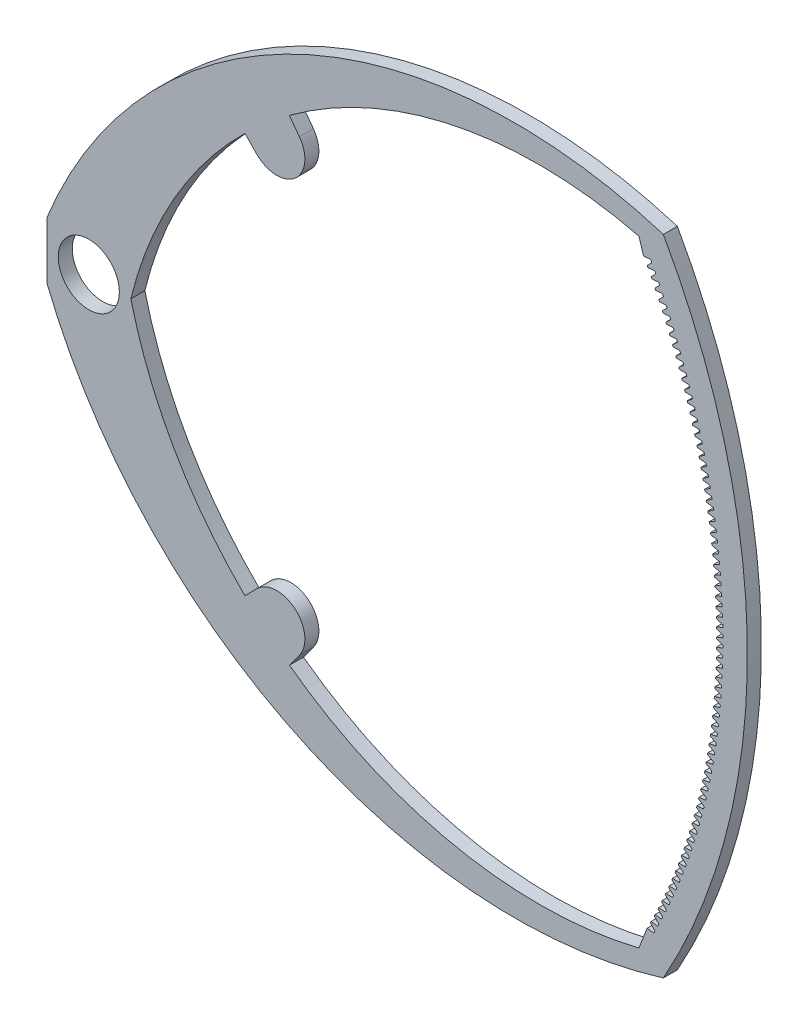
SolidWorks part; units mm, degrees
ref_plane "Plane1" through (0, 0, 0) normal (0, 0, 1) x (1, 0, 0)
ref_plane "Plane2" through (0, 0, 0) normal (0, 1, 0) x (1, 0, 0)
ref_plane "Plane3" through (0, 0, 0) normal (1, 0, 0) x (0, 0, -1)
sketch "Sketch3" plane through (0, 0, 0) normal (0, 0, 1) x (1, 0, 0)
  line L0 (0, 0) -> (305.6191, 0) construction
  line L2 (196.2779, 110) -> (205.0013, 114.8889) construction
  line L5 (-15, -10) -> (-15, 10)
  line L12 (55.7183, 71.4371) -> (59.917, 67.151)
  line L13 (59.917, 67.151) -> (75.1416, 80.1207) construction
  line L14 (75.1416, 80.1207) -> (71.5772, 84.9472)
  line L15 (71.5772, 84.9472) -> (38.0851, 60.2137) construction
  line L16 (55.7183, 71.4371) -> (7.4774, 24.1803) construction
  line L17 (75.1416, -80.1207) -> (71.5772, -84.9472)
  line L18 (55.7183, -71.4371) -> (59.917, -67.151)
  line L19 (226.2435, 1.7084) -> (223.986, 2.5016)
  line L20 (224, 0) -> (226.2485, 0.8184)
  line L21 (224.9781, 3.1415) -> (0, 0) construction
  line L22 (223.9782, 3.1275) -> (226.215, 3.9772)
  line L23 (226.1976, 4.8671) -> (223.9293, 5.6287)
  line L24 (223.9127, 6.2544) -> (226.1375, 7.1353)
  line L25 (226.1076, 8.0248) -> (223.8289, 8.7547)
  line L26 (223.8035, 9.3801) -> (226.0158, 10.292)
  line L27 (225.9736, 11.181) -> (223.6848, 11.879)
  line L28 (223.6507, 12.504) -> (225.8501, 13.4467)
  line L29 (225.7954, 14.335) -> (223.4971, 15.001)
  line L30 (223.4543, 15.6255) -> (225.6403, 16.5987)
  line L31 (225.5733, 17.4862) -> (223.2659, 18.12)
  line L32 (223.2144, 18.7438) -> (225.3866, 19.7475)
  line L33 (225.3071, 20.634) -> (222.9911, 21.2355)
  line L34 (222.9309, 21.8586) -> (225.0889, 22.8925)
  line L35 (224.9971, 23.7777) -> (222.6729, 24.3469)
  line L36 (222.604, 24.969) -> (224.7473, 26.033)
  line L37 (224.6431, 26.9169) -> (222.3113, 27.4535)
  line L38 (222.2337, 28.0746) -> (224.3619, 29.1684)
  line L39 (224.2454, 30.0508) -> (221.9063, 30.5548)
  line L40 (221.82, 31.1748) -> (223.9328, 32.2981)
  line L41 (223.804, 33.1788) -> (221.4581, 33.6501)
  line L42 (221.3632, 34.2688) -> (223.46, 35.4216)
  line L43 (223.3189, 36.3003) -> (220.9666, 36.7389)
  line L44 (220.8631, 37.3562) -> (222.9437, 38.5381)
  line L45 (222.7903, 39.4148) -> (220.4321, 39.8205)
  line L46 (220.32, 40.4363) -> (222.3839, 41.6471)
  line L47 (222.2183, 42.5216) -> (219.8547, 42.8943)
  line L48 (219.734, 43.5085) -> (221.7807, 44.748)
  line L49 (221.6029, 45.6201) -> (219.2343, 45.9598)
  line L50 (219.1051, 46.5722) -> (221.1343, 47.8402)
  line L51 (220.9444, 48.7097) -> (218.5713, 49.0163)
  line L52 (218.4335, 49.6269) -> (220.4448, 50.9231)
  line L53 (220.2428, 51.7899) -> (217.8656, 52.0632)
  line L54 (217.7193, 52.6718) -> (219.7123, 53.996)
  line L55 (219.4982, 54.8599) -> (217.1174, 55.1)
  line L56 (216.9626, 55.7065) -> (218.937, 57.0584)
  line L57 (218.7108, 57.9192) -> (216.327, 58.1261)
  line L58 (216.1637, 58.7304) -> (218.119, 60.1097)
  line L59 (217.8808, 60.9672) -> (215.4943, 61.1408)
  line L60 (215.3226, 61.7428) -> (217.2585, 63.1492)
  line L61 (217.0084, 64.0034) -> (214.6196, 64.1436)
  line L62 (214.4396, 64.7431) -> (216.3556, 66.1765)
  line L63 (216.0936, 67.0271) -> (213.7031, 67.1339)
  line L64 (213.5147, 67.7309) -> (215.4105, 69.1908)
  line L65 (215.1367, 70.0377) -> (212.745, 70.1112)
  line L66 (212.5482, 70.7054) -> (214.4235, 72.1917)
  line L67 (214.1378, 73.0346) -> (211.7453, 73.0747)
  line L68 (211.5403, 73.6661) -> (213.3946, 75.1785)
  line L69 (213.0972, 76.0173) -> (210.7044, 76.024)
  line L70 (210.4911, 76.6125) -> (212.3242, 78.1506)
  line L71 (212.0151, 78.9852) -> (209.6224, 78.9585)
  line L72 (209.401, 79.544) -> (211.2123, 81.1075)
  line L73 (210.8916, 81.9377) -> (208.4995, 81.8776)
  line L74 (208.2699, 82.4599) -> (210.0593, 84.0486)
  line L75 (209.727, 84.8742) -> (207.336, 84.7807)
  line L76 (207.0983, 85.3598) -> (208.8653, 86.9733)
  line L77 (208.5216, 87.7942) -> (206.1321, 87.6673)
  line L78 (205.8863, 88.243) -> (207.6306, 89.881)
  line L79 (207.2754, 90.6971) -> (204.888, 90.5368)
  line L80 (204.6342, 91.109) -> (206.3554, 92.7712)
  line L81 (205.9889, 93.5822) -> (203.6039, 93.3887)
  line L82 (203.3422, 93.9573) -> (205.04, 95.6433)
  line L83 (204.6622, 96.4492) -> (202.2802, 96.2223)
  line L84 (202.0105, 96.7872) -> (203.6847, 98.4968)
  line L85 (203.2956, 99.2973) -> (200.917, 99.0372)
  line L86 (200.6394, 99.5983) -> (202.2896, 101.3311)
  line L87 (201.8894, 102.1261) -> (199.5146, 101.8328)
  line L88 (199.2293, 102.3899) -> (200.8551, 104.1456)
  line L89 (200.4438, 104.9349) -> (198.0734, 104.6085)
  line L90 (197.7803, 105.1616) -> (196.2779, 110)
  line L91 (226.2453, -1.4506) -> (223.9991, -0.626)
  line L92 (223.9782, -3.1275) -> (226.2379, -2.3406)
  line L93 (226.203, -4.6094) -> (223.9686, -3.7534)
  line L94 (223.9127, -6.2544) -> (226.1832, -5.4992)
  line L95 (226.1166, -7.7672) -> (223.8943, -6.8801)
  line L96 (223.8035, -9.3801) -> (226.0843, -8.6566)
  line L97 (225.9861, -10.9235) -> (223.7764, -10.0055)
  line L98 (223.6507, -12.504) -> (225.9414, -11.8124)
  line L99 (225.8116, -14.0777) -> (223.6149, -13.1289)
  line L100 (223.4543, -15.6255) -> (225.7545, -14.9659)
  line L101 (225.593, -17.2292) -> (223.4098, -16.2498)
  line L102 (223.2144, -18.7438) -> (225.5235, -18.1165)
  line L103 (225.3305, -20.3773) -> (223.1612, -19.3675)
  line L104 (222.9309, -21.8586) -> (225.2486, -21.2635)
  line L105 (225.024, -23.5214) -> (222.869, -22.4814)
  line L106 (222.604, -24.969) -> (224.9297, -24.4064)
  line L107 (224.6737, -26.6609) -> (222.5334, -25.591)
  line L108 (222.2337, -28.0746) -> (224.5671, -27.5445)
  line L109 (224.2795, -29.7952) -> (222.1544, -28.6955)
  line L110 (221.82, -31.1748) -> (224.1606, -30.6773)
  line L111 (223.8417, -32.9238) -> (221.7321, -31.7945)
  line L112 (221.3632, -34.2688) -> (223.7104, -33.8041)
  line L113 (223.3602, -36.0459) -> (221.2665, -34.8873)
  line L114 (220.8631, -37.3562) -> (223.2166, -36.9242)
  line L115 (222.8351, -39.161) -> (220.7579, -37.9732)
  line L116 (220.32, -40.4363) -> (222.6793, -40.0372)
  line L117 (222.2666, -42.2684) -> (220.2062, -41.0518)
  line L118 (219.734, -43.5085) -> (222.0986, -43.1424)
  line L119 (221.6548, -45.3676) -> (219.6115, -44.1224)
  line L120 (219.1051, -46.5722) -> (221.4746, -46.2392)
  line L121 (220.9997, -48.458) -> (218.9741, -47.1843)
  line L122 (218.4335, -49.6269) -> (220.8074, -49.327)
  line L123 (220.3016, -51.5389) -> (218.2939, -50.2371)
  line L124 (217.7193, -52.6718) -> (220.0972, -52.4051)
  line L125 (219.5606, -54.6098) -> (217.5712, -53.28)
  line L126 (216.9626, -55.7065) -> (219.344, -55.473)
  line L127 (218.7767, -57.67) -> (216.8061, -56.3126)
  line L128 (216.1637, -58.7304) -> (218.5481, -58.5301)
  line L129 (217.9502, -60.719) -> (215.9987, -59.3342)
  line L130 (215.3226, -61.7428) -> (217.7096, -61.5759)
  line L131 (217.0811, -63.7561) -> (215.1492, -62.3442)
  line L132 (214.4396, -64.7431) -> (216.8287, -64.6096)
  line L133 (216.1698, -66.7808) -> (214.2578, -65.3421)
  line L134 (213.5147, -67.7309) -> (215.9054, -67.6307)
  line L135 (215.2163, -69.7925) -> (213.3246, -68.3272)
  line L136 (212.5482, -70.7054) -> (214.9401, -70.6386)
  line L137 (214.2209, -72.7906) -> (212.3498, -71.2991)
  line L138 (211.5403, -73.6661) -> (213.9329, -73.6327)
  line L139 (213.1837, -75.7745) -> (211.3336, -74.257)
  line L140 (210.4911, -76.6125) -> (212.884, -76.6125)
  line L141 (212.1049, -78.7436) -> (210.2762, -77.2004)
  line L142 (209.401, -79.544) -> (211.7935, -79.5774)
  line L143 (210.9848, -81.6974) -> (209.1779, -80.1288)
  line L144 (208.2699, -82.4599) -> (210.6618, -82.5267)
  line L145 (209.8236, -84.6352) -> (208.0387, -83.0416)
  line L146 (207.0983, -85.3598) -> (209.489, -85.46)
  line L147 (208.6215, -87.5566) -> (206.859, -85.9382)
  line L148 (205.8863, -88.243) -> (208.2754, -88.3766)
  line L149 (207.3786, -90.4608) -> (205.6389, -88.818)
  line L150 (204.6342, -91.109) -> (207.0212, -91.2759)
  line L151 (206.0954, -93.3475) -> (204.3788, -91.6805)
  line L152 (203.3422, -93.9573) -> (205.7266, -94.1575)
  line L153 (204.772, -96.2159) -> (203.0788, -94.5251)
  line L154 (202.0105, -96.7872) -> (204.3919, -97.0207)
  line L155 (203.4086, -99.0656) -> (201.7392, -97.3513)
  line L156 (200.6394, -99.5983) -> (203.0173, -99.865)
  line L157 (202.0056, -101.896) -> (200.3603, -100.1586)
  line L158 (199.2293, -102.3899) -> (201.6032, -102.6898)
  line L159 (199.2293, -102.3899) -> (196.2779, -110)
  arc A0 (205.0013, -114.8889) -> (205.0013, 114.8889) centre (0, 0) ccw
  arc A1 (220.8879, 48.9651) -> (225.6282, -16.7623) centre (0, 0) cw construction
  arc A2 (196.2779, 110) -> (196.2779, -110) centre (0, 0) cw construction
  circle A3 centre (0, 0) radius 10.9
  circle A4 centre (100, 0) radius 70 construction
  arc A5 (15, 0) -> (196.2779, 110) centre (160.6858, -35.7162) cw construction
  arc A6 (-15, 10) -> (205.0013, 114.8889) centre (152.0118, -57.1347) cw
  arc A7 (-15, -10) -> (205.0013, -114.8889) centre (152.0118, 57.1347) ccw
  arc A9 (15, 0) -> (55.7183, 71.4371) centre (160.6858, -35.7162) cw
  arc A10 (71.5772, 84.9472) -> (196.2779, 110) centre (160.6858, -35.7162) cw
  arc A11 (75.1416, 80.1207) -> (59.917, 67.151) centre (67.0779, 74.1658) cw
  arc A12 (100, 0) -> (46.366, 88.6013) centre (0, 0) ccw construction
  arc A13 (71.5772, -84.9472) -> (196.2779, -110) centre (160.6858, 35.7162) ccw
  arc A14 (75.1416, -80.1207) -> (59.917, -67.151) centre (67.0779, -74.1658) ccw
  arc A15 (15, 0) -> (55.7183, -71.4371) centre (160.6858, 35.7162) ccw
  arc A16 (223.2671, -18.1055) -> (218.4, 49.774) centre (0, 0) ccw construction
  arc A17 (223.9782, 3.1275) -> (223.986, 2.5016) centre (0, 0) cw
  arc A18 (226.2485, 0.8184) -> (226.2435, 1.7084) centre (0, 0) ccw
  arc A19 (226.215, 3.9772) -> (226.1976, 4.8671) centre (0, 0) ccw
  arc A20 (223.9127, 6.2544) -> (223.9293, 5.6287) centre (0, 0) cw
  arc A21 (226.1375, 7.1353) -> (226.1076, 8.0248) centre (0, 0) ccw
  arc A22 (223.8035, 9.3801) -> (223.8289, 8.7547) centre (0, 0) cw
  arc A23 (226.0158, 10.292) -> (225.9736, 11.181) centre (0, 0) ccw
  arc A24 (223.6507, 12.504) -> (223.6848, 11.879) centre (0, 0) cw
  arc A25 (225.8501, 13.4467) -> (225.7954, 14.335) centre (0, 0) ccw
  arc A26 (223.4543, 15.6255) -> (223.4971, 15.001) centre (0, 0) cw
  arc A27 (225.6403, 16.5987) -> (225.5733, 17.4862) centre (0, 0) ccw
  arc A28 (223.2144, 18.7438) -> (223.2659, 18.12) centre (0, 0) cw
  arc A29 (225.3866, 19.7475) -> (225.3071, 20.634) centre (0, 0) ccw
  arc A30 (222.9309, 21.8586) -> (222.9911, 21.2355) centre (0, 0) cw
  arc A31 (225.0889, 22.8925) -> (224.9971, 23.7777) centre (0, 0) ccw
  arc A32 (222.604, 24.969) -> (222.6729, 24.3469) centre (0, 0) cw
  arc A33 (224.7473, 26.033) -> (224.6431, 26.9169) centre (0, 0) ccw
  arc A34 (222.2337, 28.0746) -> (222.3113, 27.4535) centre (0, 0) cw
  arc A35 (224.3619, 29.1684) -> (224.2454, 30.0508) centre (0, 0) ccw
  arc A36 (221.82, 31.1748) -> (221.9063, 30.5548) centre (0, 0) cw
  arc A37 (223.9328, 32.2981) -> (223.804, 33.1788) centre (0, 0) ccw
  arc A38 (221.3632, 34.2688) -> (221.4581, 33.6501) centre (0, 0) cw
  arc A39 (223.46, 35.4216) -> (223.3189, 36.3003) centre (0, 0) ccw
  arc A40 (220.8631, 37.3562) -> (220.9666, 36.7389) centre (0, 0) cw
  arc A41 (222.9437, 38.5381) -> (222.7903, 39.4148) centre (0, 0) ccw
  arc A42 (220.32, 40.4363) -> (220.4321, 39.8205) centre (0, 0) cw
  arc A43 (222.3839, 41.6471) -> (222.2183, 42.5216) centre (0, 0) ccw
  arc A44 (219.734, 43.5085) -> (219.8547, 42.8943) centre (0, 0) cw
  arc A45 (221.7807, 44.748) -> (221.6029, 45.6201) centre (0, 0) ccw
  arc A46 (219.1051, 46.5722) -> (219.2343, 45.9598) centre (0, 0) cw
  arc A47 (221.1343, 47.8402) -> (220.9444, 48.7097) centre (0, 0) ccw
  arc A48 (218.4335, 49.6269) -> (218.5713, 49.0163) centre (0, 0) cw
  arc A49 (220.4448, 50.9231) -> (220.2428, 51.7899) centre (0, 0) ccw
  arc A50 (217.7193, 52.6718) -> (217.8656, 52.0632) centre (0, 0) cw
  arc A51 (219.7123, 53.996) -> (219.4982, 54.8599) centre (0, 0) ccw
  arc A52 (216.9626, 55.7065) -> (217.1174, 55.1) centre (0, 0) cw
  arc A53 (218.937, 57.0584) -> (218.7108, 57.9192) centre (0, 0) ccw
  arc A54 (216.1637, 58.7304) -> (216.327, 58.1261) centre (0, 0) cw
  arc A55 (218.119, 60.1097) -> (217.8808, 60.9672) centre (0, 0) ccw
  arc A56 (215.3226, 61.7428) -> (215.4943, 61.1408) centre (0, 0) cw
  arc A57 (217.2585, 63.1492) -> (217.0084, 64.0034) centre (0, 0) ccw
  arc A58 (214.4396, 64.7431) -> (214.6196, 64.1436) centre (0, 0) cw
  arc A59 (216.3556, 66.1765) -> (216.0936, 67.0271) centre (0, 0) ccw
  arc A60 (213.5147, 67.7309) -> (213.7031, 67.1339) centre (0, 0) cw
  arc A61 (215.4105, 69.1908) -> (215.1367, 70.0377) centre (0, 0) ccw
  arc A62 (212.5482, 70.7054) -> (212.745, 70.1112) centre (0, 0) cw
  arc A63 (214.4235, 72.1917) -> (214.1378, 73.0346) centre (0, 0) ccw
  arc A64 (211.5403, 73.6661) -> (211.7453, 73.0747) centre (0, 0) cw
  arc A65 (213.3946, 75.1785) -> (213.0972, 76.0173) centre (0, 0) ccw
  arc A66 (210.4911, 76.6125) -> (210.7044, 76.024) centre (0, 0) cw
  arc A67 (212.3242, 78.1506) -> (212.0151, 78.9852) centre (0, 0) ccw
  arc A68 (209.401, 79.544) -> (209.6224, 78.9585) centre (0, 0) cw
  arc A69 (211.2123, 81.1075) -> (210.8916, 81.9377) centre (0, 0) ccw
  arc A70 (208.2699, 82.4599) -> (208.4995, 81.8776) centre (0, 0) cw
  arc A71 (210.0593, 84.0486) -> (209.727, 84.8742) centre (0, 0) ccw
  arc A72 (207.0983, 85.3598) -> (207.336, 84.7807) centre (0, 0) cw
  arc A73 (208.8653, 86.9733) -> (208.5216, 87.7942) centre (0, 0) ccw
  arc A74 (205.8863, 88.243) -> (206.1321, 87.6673) centre (0, 0) cw
  arc A75 (207.6306, 89.881) -> (207.2754, 90.6971) centre (0, 0) ccw
  arc A76 (204.6342, 91.109) -> (204.888, 90.5368) centre (0, 0) cw
  arc A77 (206.3554, 92.7712) -> (205.9889, 93.5822) centre (0, 0) ccw
  arc A78 (203.3422, 93.9573) -> (203.6039, 93.3887) centre (0, 0) cw
  arc A79 (205.04, 95.6433) -> (204.6622, 96.4492) centre (0, 0) ccw
  arc A80 (202.0105, 96.7872) -> (202.2802, 96.2223) centre (0, 0) cw
  arc A81 (203.6847, 98.4968) -> (203.2956, 99.2973) centre (0, 0) ccw
  arc A82 (200.6394, 99.5983) -> (200.917, 99.0372) centre (0, 0) cw
  arc A83 (202.2896, 101.3311) -> (201.8894, 102.1261) centre (0, 0) ccw
  arc A84 (199.2293, 102.3899) -> (199.5146, 101.8328) centre (0, 0) cw
  arc A85 (200.8551, 104.1456) -> (200.4438, 104.9349) centre (0, 0) ccw
  arc A86 (197.7803, 105.1616) -> (198.0734, 104.6085) centre (0, 0) cw
  arc A87 (224, 0) -> (223.9991, -0.626) centre (0, 0) cw
  arc A88 (226.2379, -2.3406) -> (226.2453, -1.4506) centre (0, 0) ccw
  arc A89 (223.9782, -3.1275) -> (223.9686, -3.7534) centre (0, 0) cw
  arc A90 (226.1832, -5.4992) -> (226.203, -4.6094) centre (0, 0) ccw
  arc A91 (223.9127, -6.2544) -> (223.8943, -6.8801) centre (0, 0) cw
  arc A92 (226.0843, -8.6566) -> (226.1166, -7.7672) centre (0, 0) ccw
  arc A93 (223.8035, -9.3801) -> (223.7764, -10.0055) centre (0, 0) cw
  arc A94 (225.9414, -11.8124) -> (225.9861, -10.9235) centre (0, 0) ccw
  arc A95 (223.6507, -12.504) -> (223.6149, -13.1289) centre (0, 0) cw
  arc A96 (225.7545, -14.9659) -> (225.8116, -14.0777) centre (0, 0) ccw
  arc A97 (223.4543, -15.6255) -> (223.4098, -16.2498) centre (0, 0) cw
  arc A98 (225.5235, -18.1165) -> (225.593, -17.2292) centre (0, 0) ccw
  arc A99 (223.2144, -18.7438) -> (223.1612, -19.3675) centre (0, 0) cw
  arc A100 (225.2486, -21.2635) -> (225.3305, -20.3773) centre (0, 0) ccw
  arc A101 (222.9309, -21.8586) -> (222.869, -22.4814) centre (0, 0) cw
  arc A102 (224.9297, -24.4064) -> (225.024, -23.5214) centre (0, 0) ccw
  arc A103 (222.604, -24.969) -> (222.5334, -25.591) centre (0, 0) cw
  arc A104 (224.5671, -27.5445) -> (224.6737, -26.6609) centre (0, 0) ccw
  arc A105 (222.2337, -28.0746) -> (222.1544, -28.6955) centre (0, 0) cw
  arc A106 (224.1606, -30.6773) -> (224.2795, -29.7952) centre (0, 0) ccw
  arc A107 (221.82, -31.1748) -> (221.7321, -31.7945) centre (0, 0) cw
  arc A108 (223.7104, -33.8041) -> (223.8417, -32.9238) centre (0, 0) ccw
  arc A109 (221.3632, -34.2688) -> (221.2665, -34.8873) centre (0, 0) cw
  arc A110 (223.2166, -36.9242) -> (223.3602, -36.0459) centre (0, 0) ccw
  arc A111 (220.8631, -37.3562) -> (220.7579, -37.9732) centre (0, 0) cw
  arc A112 (222.6793, -40.0372) -> (222.8351, -39.161) centre (0, 0) ccw
  arc A113 (220.32, -40.4363) -> (220.2062, -41.0518) centre (0, 0) cw
  arc A114 (222.0986, -43.1424) -> (222.2666, -42.2684) centre (0, 0) ccw
  arc A115 (219.734, -43.5085) -> (219.6115, -44.1224) centre (0, 0) cw
  arc A116 (221.4746, -46.2392) -> (221.6548, -45.3676) centre (0, 0) ccw
  arc A117 (219.1051, -46.5722) -> (218.9741, -47.1843) centre (0, 0) cw
  arc A118 (220.8074, -49.327) -> (220.9997, -48.458) centre (0, 0) ccw
  arc A119 (218.4335, -49.6269) -> (218.2939, -50.2371) centre (0, 0) cw
  arc A120 (220.0972, -52.4051) -> (220.3016, -51.5389) centre (0, 0) ccw
  arc A121 (217.7193, -52.6718) -> (217.5712, -53.28) centre (0, 0) cw
  arc A122 (219.344, -55.473) -> (219.5606, -54.6098) centre (0, 0) ccw
  arc A123 (216.9626, -55.7065) -> (216.8061, -56.3126) centre (0, 0) cw
  arc A124 (218.5481, -58.5301) -> (218.7767, -57.67) centre (0, 0) ccw
  arc A125 (216.1637, -58.7304) -> (215.9987, -59.3342) centre (0, 0) cw
  arc A126 (217.7096, -61.5759) -> (217.9502, -60.719) centre (0, 0) ccw
  arc A127 (215.3226, -61.7428) -> (215.1492, -62.3442) centre (0, 0) cw
  arc A128 (216.8287, -64.6096) -> (217.0811, -63.7561) centre (0, 0) ccw
  arc A129 (214.4396, -64.7431) -> (214.2578, -65.3421) centre (0, 0) cw
  arc A130 (215.9054, -67.6307) -> (216.1698, -66.7808) centre (0, 0) ccw
  arc A131 (213.5147, -67.7309) -> (213.3246, -68.3272) centre (0, 0) cw
  arc A132 (214.9401, -70.6386) -> (215.2163, -69.7925) centre (0, 0) ccw
  arc A133 (212.5482, -70.7054) -> (212.3498, -71.2991) centre (0, 0) cw
  arc A134 (213.9329, -73.6327) -> (214.2209, -72.7906) centre (0, 0) ccw
  arc A135 (211.5403, -73.6661) -> (211.3336, -74.257) centre (0, 0) cw
  arc A136 (212.884, -76.6125) -> (213.1837, -75.7745) centre (0, 0) ccw
  arc A137 (210.4911, -76.6125) -> (210.2762, -77.2004) centre (0, 0) cw
  arc A138 (211.7935, -79.5774) -> (212.1049, -78.7436) centre (0, 0) ccw
  arc A139 (209.401, -79.544) -> (209.1779, -80.1288) centre (0, 0) cw
  arc A140 (210.6618, -82.5267) -> (210.9848, -81.6974) centre (0, 0) ccw
  arc A141 (208.2699, -82.4599) -> (208.0387, -83.0416) centre (0, 0) cw
  arc A142 (209.489, -85.46) -> (209.8236, -84.6352) centre (0, 0) ccw
  arc A143 (207.0983, -85.3598) -> (206.859, -85.9382) centre (0, 0) cw
  arc A144 (208.2754, -88.3766) -> (208.6215, -87.5566) centre (0, 0) ccw
  arc A145 (205.8863, -88.243) -> (205.6389, -88.818) centre (0, 0) cw
  arc A146 (207.0212, -91.2759) -> (207.3786, -90.4608) centre (0, 0) ccw
  arc A147 (204.6342, -91.109) -> (204.3788, -91.6805) centre (0, 0) cw
  arc A148 (205.7266, -94.1575) -> (206.0954, -93.3475) centre (0, 0) ccw
  arc A149 (203.3422, -93.9573) -> (203.0788, -94.5251) centre (0, 0) cw
  arc A150 (204.3919, -97.0207) -> (204.772, -96.2159) centre (0, 0) ccw
  arc A151 (202.0105, -96.7872) -> (201.7392, -97.3513) centre (0, 0) cw
  arc A152 (203.0173, -99.865) -> (203.4086, -99.0656) centre (0, 0) ccw
  arc A153 (200.6394, -99.5983) -> (200.3603, -100.1586) centre (0, 0) cw
  arc A154 (201.6032, -102.6898) -> (202.0056, -101.896) centre (0, 0) ccw
  point P9 (224.9997, 0.3639)
  point P41 (224.9897, 2.149)
  point P218 (0, 0)
  point P355 (0, 0)
  dimension "D1" = 10
  dimension "D2" = 140
  dimension "D4" = 15
  dimension "D7" = 20
  dimension "D9" = 150
  dimension "D10" = 180
  dimension "D11" = 10
  dimension "D13" = 1
  dimension "D14" = 1.25
  dimension "D15" = 225
  dimension "D16" = 0.8
  dimension "D21" = 21.8
  dimension "D3" = 100
  dimension "D5" = 15
  dimension "D6" = 20
  dimension "D8" = 6
  dimension "D12" = 20
  dimension "D17" = 0.89
  dimension "D19" = 110
  dimension "D20" = 35
  dimension "D18" = 35
extrude "Boss-Extrude2" add sketch "Sketch3" along normal blind 5
